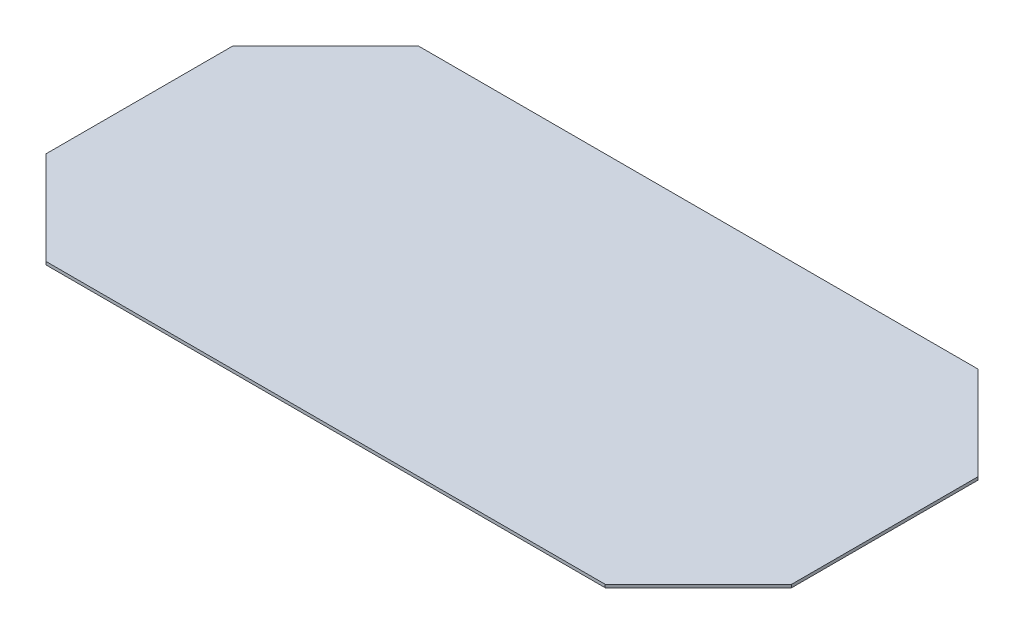
SolidWorks part; units mm, degrees
ref_plane "Front Plane" through (0, 0, 0) normal (0, 0, 1) x (1, 0, 0)
ref_plane "Top Plane" through (0, 0, 0) normal (0, 1, 0) x (1, 0, 0)
ref_plane "Right Plane" through (0, 0, 0) normal (1, 0, 0) x (0, 0, -1)
sketch "Sketch1" plane through (0, 0, 0) normal (0, 1, 0) x (1, 0, 0)
  line L1 (-123.19, 61.595) -> (123.19, 61.595)
  line L2 (-123.19, 61.595) -> (-123.19, -61.595)
  line L3 (-123.19, -61.595) -> (123.19, -61.595)
  line L4 (123.19, 61.595) -> (123.19, -61.595)
  line L5 (-123.19, 61.595) -> (123.19, -61.595) construction
  line L6 (-123.19, -61.595) -> (123.19, 61.595) construction
  point P0 (0, 0)
  dimension "D1" = 246.38
  dimension "D2" = 123.19
extrude "Boss-Extrude1" add sketch "Sketch1" along normal blind 1
chamfer "Chamfer1" distance 30.7975 angle 45 4 edges at (123.19, 0.5, 61.595) (123.19, 0.5, -61.595) (-123.19, 0.5, 61.595) (-123.19, 0.5, -61.595)
